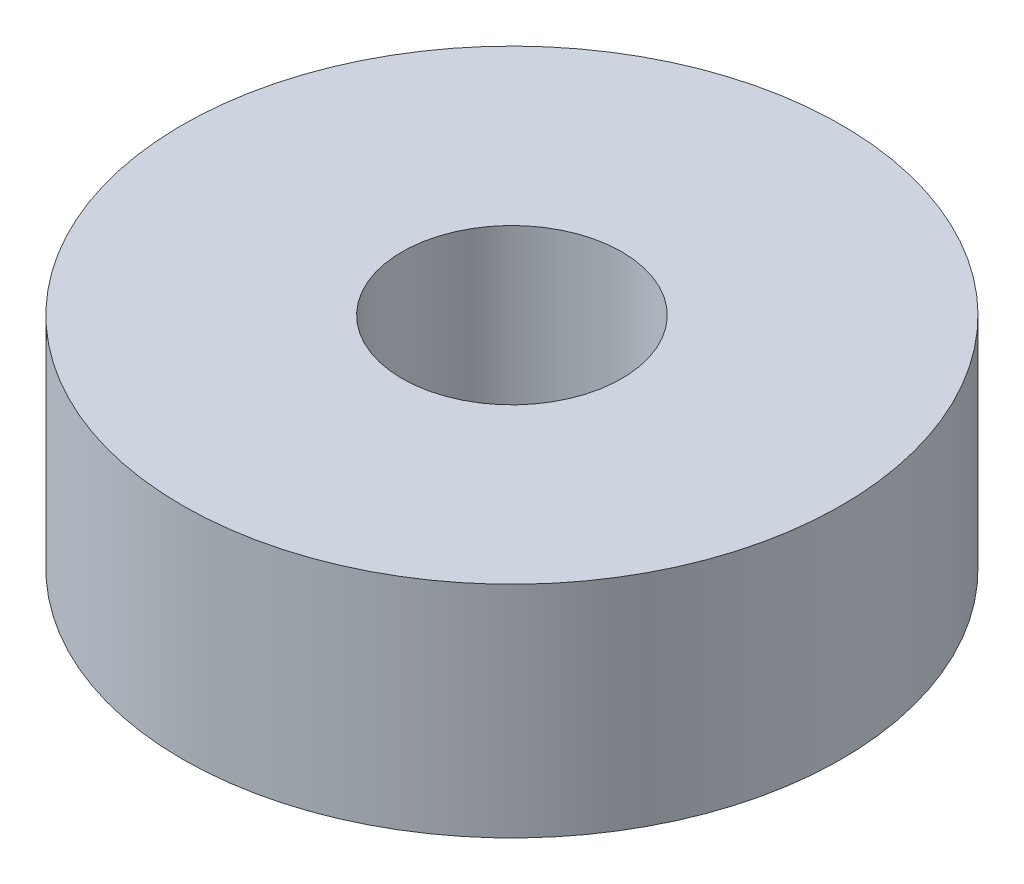
SolidWorks part; units mm, degrees
material "Titanio Ti-8Al-1Mo-1V"
ref_plane "Alzado" through (0, 0, 0) normal (0, 0, 1) x (1, 0, 0)
ref_plane "Planta" through (0, 0, 0) normal (0, 1, 0) x (1, 0, 0)
ref_plane "Vista lateral" through (0, 0, 0) normal (1, 0, 0) x (0, 0, -1)
sketch "Croquis1" plane through (0, 0, 0) normal (0, 1, 0) x (1, 0, 0)
  circle A0 centre (0, 0) radius 15
  circle A1 centre (0, 0) radius 5
  dimension "D1" = 30
  dimension "D2" = 10
extrude "Saliente-Extruir1" add sketch "Croquis1" along normal blind 10
